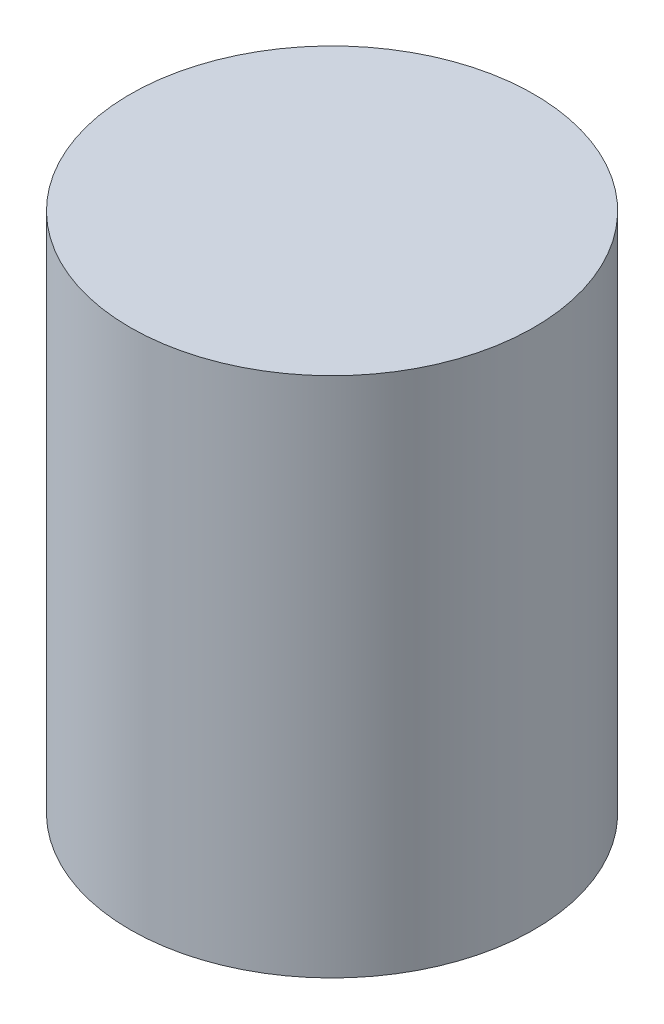
SolidWorks part; units mm, degrees
ref_plane "Front Plane" through (0, 0, 0) normal (0, 0, 1) x (1, 0, 0)
ref_plane "Top Plane" through (0, 0, 0) normal (0, 1, 0) x (1, 0, 0)
ref_plane "Right Plane" through (0, 0, 0) normal (1, 0, 0) x (0, 0, -1)
sketch "Sketch1" plane through (0, 0, 0) normal (0, 1, 0) x (1, 0, 0)
  circle A0 centre (0, 0) radius 3.485
  dimension "D1" = 6.97
extrude "Boss-Extrude1" add sketch "Sketch1" along normal blind 9
sketch "Sketch2" plane through (0, 0, 0) normal (1, 0, 0) x (0, 0, -1)
  line L0 (0, 0) -> (0, 11.1391) construction
  line L1 (-4.8557, 4) -> (5.1902, 4) construction
  line L2 (3.485, 9) -> (-3.485, 9) construction
  line L3 (-2, 11.4755) -> (-2, -5.7241) construction
  line L4 (-2.6526, 6.1909) -> (-2.6526, 4)
  line L5 (-1.1526, 5.4514) -> (-1.1526, 4)
  line L6 (-1.1526, 4) -> (0, 4)
  line L7 (-2.6526, 4) -> (-3.5114, 4)
  circle A0 centre (-2, 7.125) radius 1.875 construction
  arc A1 (-2.6526, 8.3363) -> (-2.6526, 5.9137) centre (-2, 7.125) cw construction
  arc A2 (-2.4155, 7.8961) -> (-2.4155, 6.3539) centre (-2, 7.125) cw
  arc A3 (-2.8898, 8.7765) -> (-2.8898, 5.4735) centre (-2, 7.125) cw
  arc A4 (-2.8898, 8.7765) -> (-2.4155, 7.8961) centre (-2.6526, 8.3363) ccw
  arc A5 (-2.4155, 6.3539) -> (-2.6526, 6.1909) centre (-2.4922, 6.2115) ccw
  arc A6 (-2.4155, 6.3539) -> (-2.8898, 5.4735) centre (-2.6526, 5.9137) ccw
  dimension "D3" = 3.75
  dimension "D4" = 1.3759
  dimension "D5" = 0.4991
  dimension "D8" = 1.5
  dimension "D1" = 5
  dimension "D2" = 2
  dimension "D6" = 0.5
  dimension "D7" = 0.5
